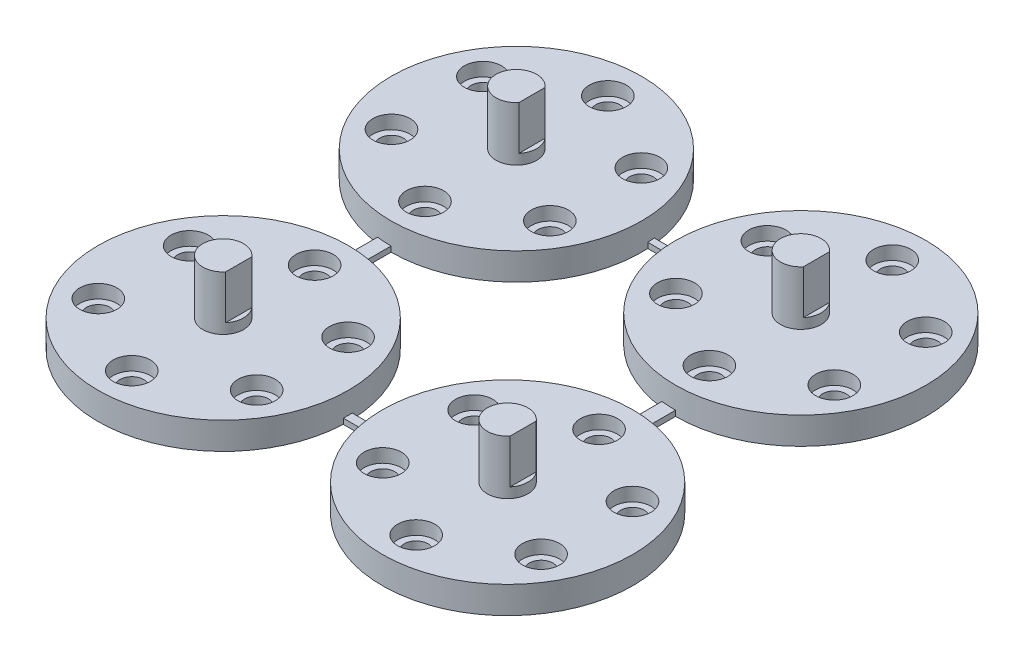
SolidWorks part; units mm, degrees
ref_plane "前视基准面" through (0, 0, 0) normal (0, 0, 1) x (1, 0, 0)
ref_plane "上视基准面" through (0, 0, 0) normal (0, 1, 0) x (1, 0, 0)
ref_plane "右视基准面" through (0, 0, 0) normal (1, 0, 0) x (0, 0, -1)
other "Configuration Table"
ref_plane "基准面1" through (0, 0, 0.9229) normal (0, 0, 1) x (1, 0, 0)
sketch "草图1" plane through (0, 0, 0.9229) normal (0, 0, 1) x (1, 0, 0)
  line L0 (19.1094, 4) -> (0.6094, 4)
  line L1 (0.6094, 4) -> (0.6094, 0)
  line L2 (0.6094, 0) -> (19.1094, 0)
  line L3 (19.1094, 0) -> (19.1094, 4)
  line L4 (0.6094, 4) -> (0.6094, 0) construction
revolve "旋转1" add sketch "草图1" angle 360 about L4
hole_wizard "M3 六角头机械螺钉的柱形沉头孔1" positions "草图7" profile "草图6" counterbore size "M3" standard "ANSI Metric" end condition through all
sketch "草图7" plane through (0, 4, 0) normal (0, 1, 0) x (1, 0, 0)
  point P0 (-11.082, -7.6729)
  point P1 (12.3007, -7.6729)
  point P2 (0.6094, 12.5771)
sketch "草图6" plane through (-11.082, 4, 7.6729) normal (1, 0, 0) x (0, 0, 1)
  line L0 (0, 0) -> (0, 4)
  line L1 (0, 4) -> (1.75, 4)
  line L3 (1.75, 4) -> (1.75, 2)
  line L4 (1.75, 2) -> (2.75, 2)
  line L5 (2.75, 2) -> (2.75, 0)
  line L7 (2.75, 0) -> (0, 0)
  line L11 (0, -6.35) -> (0, 107.95) construction
  dimension "通孔孔直径" = 3.5
  dimension "通孔孔深度" = 4
  dimension "柱形沉头孔直径" = 5.5
  dimension "柱形沉头孔深度" = 2
sketch "草图9" plane through (0, 0, 0) normal (0, -1, 0) x (1, 0, 0)
  circle A1 centre (0.6094, 0.9229) radius 4.0788
extrude "凸台-拉伸2" add sketch "草图9" against normal blind 4
sketch "草图10" plane through (0, 4, 0) normal (0, 1, 0) x (1, 0, 0)
  circle A0 centre (0.6094, -0.9229) radius 3
  point P0 (0.6094, -0.9229)
  dimension "D1" = 6
extrude "凸台-拉伸3" add sketch "草图10" along normal blind 8
sketch "草图11" plane through (0, 12, 0) normal (0, 1, 0) x (1, 0, 0)
  line L0 (2.9059, 1.0074) -> (2.9059, -2.8532)
  circle A0 centre (0.6094, -0.9229) radius 3 construction
  circle A1 centre (0.6094, -0.9229) radius 3 construction
  arc A2 (2.9059, -2.8532) -> (2.9059, 1.0074) centre (0.6094, -0.9229) ccw
extrude "切除-拉伸2" cut sketch "草图11" against normal blind 6.5
pattern_circular "阵列(圆周)1" count 3 every 60 about axis through (0.6094, 0, 0.9229) along (0, 1, 0) of "M3 六角头机械螺钉的柱形沉头孔1"
move or copy body "实体-移动/复制3"
sketch "草图13" plane through (0, 0, 0) normal (0, -1, 0) x (1, 0, 0)
  line L27 (-1.5166, 25.8415) -> (0.6094, 25.8415)
  line L28 (-1.5166, 25.8415) -> (-1.5166, 18.309)
  line L29 (-1.5166, 18.309) -> (0.6094, 18.309)
  line L30 (0.6094, 25.8415) -> (0.6094, 18.309)
  circle A0 centre (0.6094, 44.2189) radius 18.5 construction
extrude "凸台-拉伸4" add sketch "草图13" against normal blind 0.8 contours L30 L29 L28 L27
move or copy body "实体-移动/复制4" bodies to move or copy 129 copy yes number of copies 1 translate (42, 0, 0)
sketch "草图14" plane through (0, 0, 0) normal (0, -1, 0) x (1, 0, 0)
  line L1 (17.7846, 44.973) -> (25.4341, 44.973)
  line L2 (17.7846, 44.973) -> (17.7846, 43.6617)
  line L3 (17.7846, 43.6617) -> (25.4341, 43.6617)
  line L4 (25.4341, 44.973) -> (25.4341, 43.6617)
  line L5 (17.7846, 0) -> (25.4341, 0)
  line L6 (17.7846, 0) -> (17.7846, -1.0333)
  line L7 (17.7846, -1.0333) -> (25.4341, -1.0333)
  line L8 (25.4341, 0) -> (25.4341, -1.0333)
extrude "凸台-拉伸5" add sketch "草图14" against normal blind 0.8 contours L1 L4 L3 L2 | L7 L8 L5 L6
